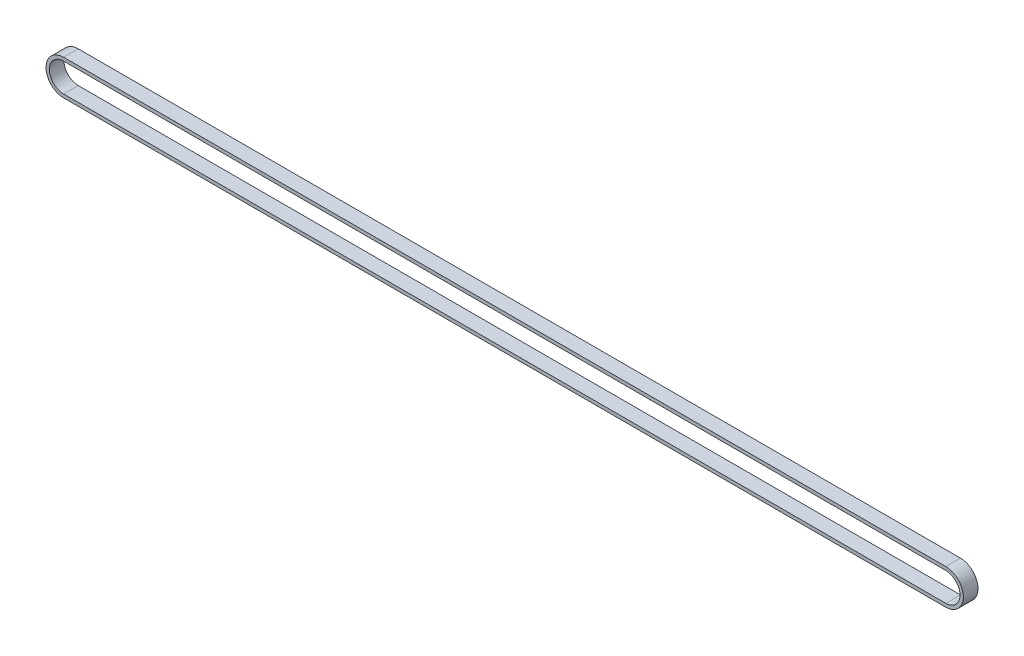
SolidWorks part; units mm, degrees
material "BUTYL"
ref_plane "Front Plane" through (0, 0, 0) normal (0, 0, 1) x (1, 0, 0)
ref_plane "Top Plane" through (0, 0, 0) normal (0, 1, 0) x (1, 0, 0)
ref_plane "Right Plane" through (0, 0, 0) normal (1, 0, 0) x (0, 0, -1)
sketch "Sketch1" plane through (0, 0, 0) normal (0, 0, 1) x (1, 0, 0)
  line L0 (0, 0) -> (361.5, 0) construction
  line L1 (0, 7.213) -> (361.5, 7.213)
  line L2 (0, -7.213) -> (361.5, -7.213)
  line L3 (0, 5.833) -> (361.5, 5.833)
  line L4 (361.5, -5.833) -> (0, -5.833)
  arc A0 (0, 7.213) -> (0, -7.213) centre (0, 0) ccw
  arc A1 (361.5, -7.213) -> (361.5, 7.213) centre (361.5, 0) ccw
  arc A2 (0, 5.833) -> (0, -5.833) centre (0, 0) ccw
  arc A3 (361.5, -5.833) -> (361.5, 5.833) centre (361.5, 0) ccw
  dimension "D2" = 1.38
  dimension "D3" = 7.213
  dimension "D1" = 361.5
extrude "Boss-Extrude1" add sketch "Sketch1" along normal blind 6
